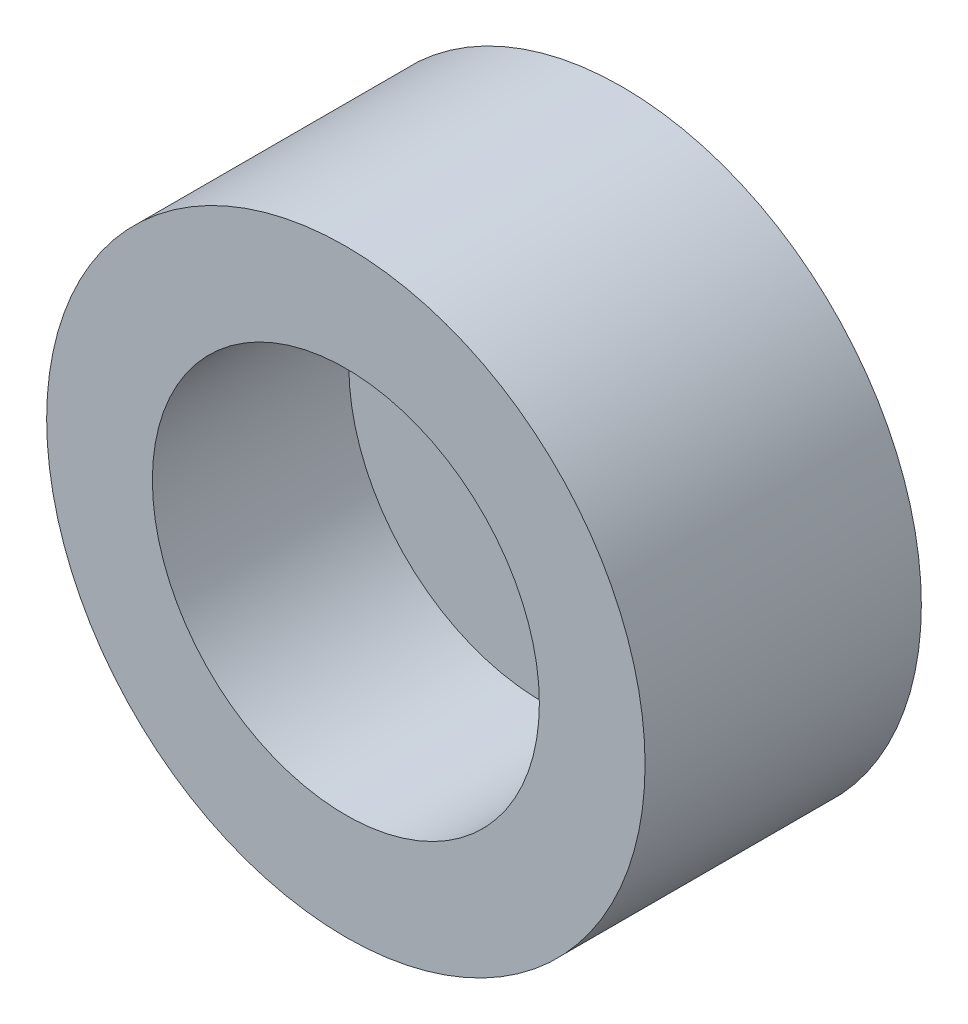
SolidWorks part; units mm, degrees
ref_plane "Front Plane" through (0, 0, 0) normal (0, 0, 1) x (1, 0, 0)
ref_plane "Top Plane" through (0, 0, 0) normal (0, 1, 0) x (1, 0, 0)
ref_plane "Right Plane" through (0, 0, 0) normal (1, 0, 0) x (0, 0, -1)
sketch "Sketch2" plane through (0, 0, 0) normal (0, 0, 1) x (1, 0, 0)
  circle A1 centre (0, 0) radius 7.5
  dimension "D2" = 15
extrude "Boss-Extrude1" add sketch "Sketch2" along normal blind 2
sketch "Sketch3" plane through (0, 0, 2) normal (0, 0, 1) x (1, 0, 0)
  circle A0 centre (0, 0) radius 4.85
  circle A1 centre (0, 0) radius 7.5
  dimension "D1" = 9.7
extrude "Boss-Extrude2" add sketch "Sketch3" along normal blind 4.925
